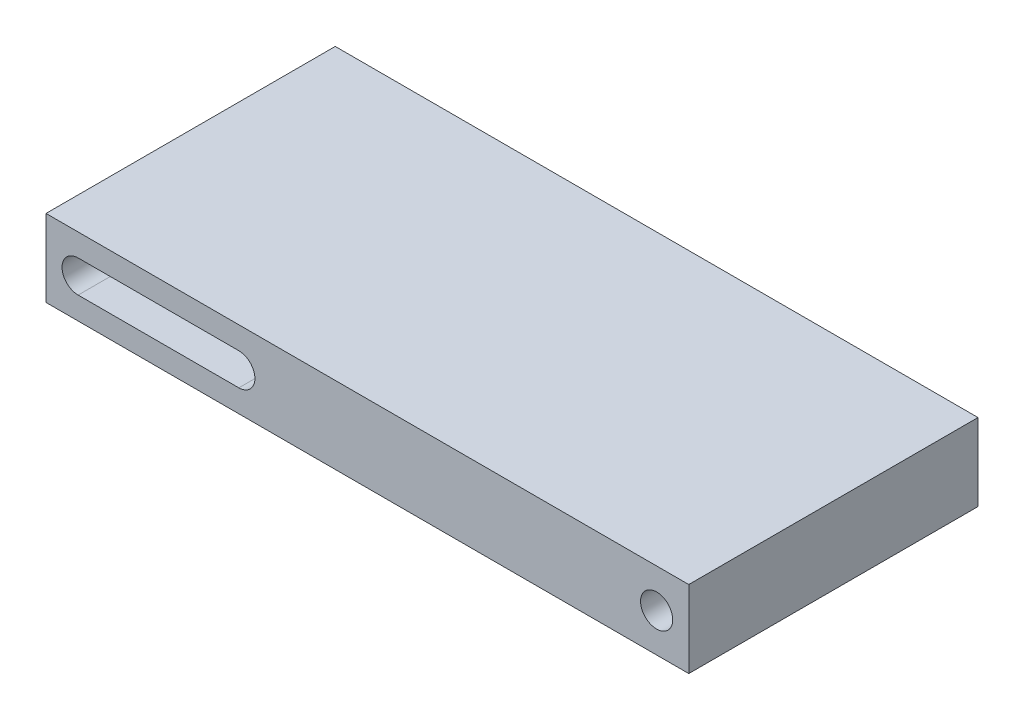
SolidWorks part; units mm, degrees
ref_plane "Front Plane" through (0, 0, 0) normal (0, 0, 1) x (1, 0, 0)
ref_plane "Top Plane" through (0, 0, 0) normal (0, 1, 0) x (1, 0, 0)
ref_plane "Right Plane" through (0, 0, 0) normal (1, 0, 0) x (0, 0, -1)
sketch "Sketch1" plane through (0, 0, 0) normal (0, 1, 0) x (1, 0, 0)
  line L1 (-50, 22.5) -> (50, 22.5)
  line L2 (-50, 22.5) -> (-50, -22.5)
  line L3 (-50, -22.5) -> (50, -22.5)
  line L4 (50, 22.5) -> (50, -22.5)
  line L5 (-50, 22.5) -> (50, -22.5) construction
  line L6 (-50, -22.5) -> (50, 22.5) construction
  point P0 (0, 0)
  dimension "D1" = 100
  dimension "D2" = 45
extrude "Boss-Extrude2" add sketch "Sketch1" along normal mid plane 12
sketch "Sketch3" plane through (0, 0, 22.5) normal (0, 0, 1) x (1, 0, 0)
  line L0 (-45, 0) -> (-20, 0) construction
  line L1 (-45, 2.5) -> (-20, 2.5)
  line L2 (-45, -2.5) -> (-20, -2.5)
  line L3 (50, 6) -> (50, -6) construction
  line L5 (-50, 6) -> (-50, -6) construction
  arc A0 (-45, 2.5) -> (-45, -2.5) centre (-45, 0) ccw
  arc A1 (-20, -2.5) -> (-20, 2.5) centre (-20, 0) ccw
  circle A2 centre (45, 0) radius 2.5
  point P3 (-32.5, 0)
  dimension "D2" = 5
  dimension "D3" = 5
  dimension "D6" = 2.5
  dimension "D1" = 65
  dimension "D4" = 5
  dimension "D5" = 25
extrude "Cut-Extrude1" cut sketch "Sketch3" against normal through all
